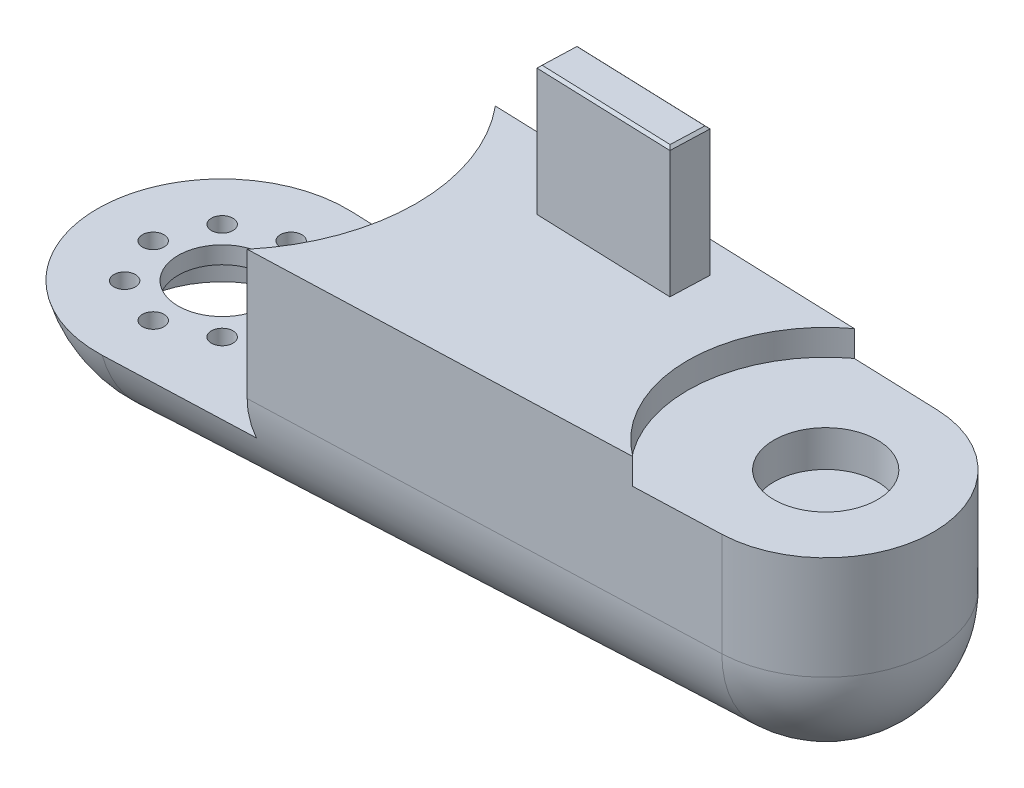
SolidWorks part; units mm, degrees
ref_plane "前视基准面" through (0, 0, 0) normal (0, 0, 1) x (1, 0, 0)
ref_plane "上视基准面" through (0, 0, 0) normal (0, 1, 0) x (1, 0, 0)
ref_plane "右视基准面" through (0, 0, 0) normal (1, 0, 0) x (0, 0, -1)
other "Configuration Table"
sketch "草图1" plane through (0, 0, 0) normal (0, 1, 0) x (1, 0, 0)
  line L2 (0.5357, -14.9904) -> (70.4464, -12.492)
  line L4 (-15, 0) -> (82.5, 0)
  arc A1 (70.4464, -12.492) -> (82.5, 0) centre (70, 0) ccw
  arc A3 (-15, 0) -> (0.5357, -14.9904) centre (0, 0) ccw
  dimension "D1" = 15
  dimension "D2" = 70
  dimension "D3" = 25
ref_axis "基准轴1" through (70, 0, 0) along (-1, 0, 0)
sketch "草图2" plane through (0, 0, 0) normal (0, 1, 0) x (1, 0, 0)
  line L0 (0.5357, 14.9904) -> (70.4464, 12.492)
  line L2 (0.5357, -14.9904) -> (70.4464, -12.492)
  line L3 (82.5, 0) -> (-15, 0)
  line L4 (0.5357, -14.9904) -> (70.4464, -12.492)
  line L5 (82.5, 0) -> (-15, 0)
  arc A2 (70.4464, -12.492) -> (82.5, 0) centre (70, 0) ccw
  arc A3 (-15, 0) -> (0.5357, -14.9904) centre (0, 0) ccw
  arc A4 (70.4464, -12.492) -> (70.4464, 12.492) centre (70, 0) ccw
  arc A5 (0.5357, 14.9904) -> (0.5357, -14.9904) centre (0, 0) ccw
  dimension "D1" = 0
extrude "凸台-拉伸1" add sketch "草图2" along normal blind 15 contours L0 A5 L5 A4 | L5 A5 L4 A4
revolve "旋转1" add sketch "草图1" angle 180 about axis through (70, 0, 0) along (-1, 0, 0)
sketch "草图3" plane through (0, 15, 0) normal (0, 1, 0) x (1, 0, 0)
  line L2 (70.4464, 12.492) -> (0.5357, 14.9904)
  line L3 (0.5357, -14.9904) -> (70.4464, -12.492)
  line L4 (17.2955, 14.3915) -> (0.5357, 14.9904)
  line L5 (0.5357, -14.9904) -> (17.2955, -14.3915)
  arc A0 (17.2955, -14.3915) -> (17.2955, 14.3915) centre (0, 0) ccw
  arc A3 (0.5357, 14.9904) -> (0.5357, -14.9904) centre (0, 0) ccw
  arc A4 (70.4464, -12.492) -> (70.4464, 12.492) centre (70, 0) ccw
  arc A5 (0.5357, 14.9904) -> (0.5357, -14.9904) centre (0, 0) ccw
  dimension "D1" = 45
  dimension "D2" = 0
extrude "切除-拉伸1" cut sketch "草图3" against normal blind 19
sketch "草图4" plane through (0, -4, 0) normal (0, 1, 0) x (1, 0, 0)
  circle A0 centre (0, 0) radius 10
  circle A1 centre (8, 0) radius 1.25
  circle A2 centre (5.6569, -5.6569) radius 1.25
  circle A3 centre (0, -8) radius 1.25
  circle A4 centre (-5.6569, -5.6569) radius 1.25
  circle A5 centre (-8, 0) radius 1.25
  circle A6 centre (-5.6569, 5.6569) radius 1.25
  circle A7 centre (0, 8) radius 1.25
  circle A8 centre (5.6569, 5.6569) radius 1.25
  circle A9 centre (0, 0) radius 5.1
  point P22 (0, 0)
  dimension "D1" = 20
  dimension "D3" = 2.5
  dimension "D5" = 10.2
  dimension "D2" = 8
  dimension "D4" = 8
ref_plane "基准面1" through (0, -6, 0) normal (0, 1, 0) x (1, 0, 0)
sketch "草图5" plane through (0, -6, 0) normal (0, 1, 0) x (1, 0, 0)
  circle A0 centre (0, 0) radius 10 construction
  circle A1 centre (0, 0) radius 10
extrude "切除-拉伸2" cut sketch "草图5" against normal through all
extrude "切除-拉伸3" cut sketch "草图4" against normal through all contours A1 | A2 | A3 | A4 | A5 | A8 | A6 | A7 | A9
sketch "草图11" plane through (0, 15, 0) normal (0, 1, 0) x (1, 0, 0)
  line L0 (70, 0) -> (93.8641, 0) construction
  line L1 (17.2955, 14.3915) -> (70.4464, 12.492) construction
  line L2 (17.2955, -14.3915) -> (70.4464, -12.492) construction
  line L3 (60.4653, 12.8487) -> (70.4464, 12.492)
  line L4 (70.4464, -12.492) -> (60.4653, -12.8487)
  arc A0 (70.4464, -12.492) -> (70.4464, 12.492) centre (70, 0) ccw construction
  arc A1 (70.4464, -12.492) -> (70.4464, 12.492) centre (70, 0) ccw
  arc A2 (60.4653, 12.8487) -> (60.4653, -12.8487) centre (70, 0) ccw
  dimension "D1" = 16
extrude "切除-拉伸5" cut sketch "草图11" against normal blind 3
sketch "草图6" plane through (0, 12, 0) normal (0, 1, 0) x (1, 0, 0)
  arc A0 (70.4464, 12.492) -> (70.4464, -12.492) centre (70, 0) ccw construction
  arc A1 (70.4464, 12.492) -> (70.4464, -12.492) centre (70, 0) ccw
  circle A2 centre (70, 0) radius 3
  circle A3 centre (70, 0) radius 6
  dimension "D1" = 6
  dimension "D2" = 12
extrude "切除-拉伸4" cut sketch "草图6" against normal blind 4.2 contours A3 A2
sketch "草图12" plane through (0, 15, 0) normal (0, 1, 0) x (1, 0, 0)
  line L1 (30.5998, 5.9109) -> (46.5896, 5.3395)
  line L3 (46.5896, 5.3395) -> (46.7503, 9.8366)
  line L8 (46.7503, 9.8366) -> (30.7605, 10.408)
  line L9 (30.7605, 10.408) -> (30.5998, 5.9109)
  line L10 (38.4535, 1.6731) -> (38.9626, 15.9198) construction
  line L11 (17.2955, 14.3915) -> (60.4653, 12.8487) construction
  line L12 (17.2955, 14.3915) -> (60.4653, 12.8487)
  dimension "D5" = 8
  dimension "D1" = 3.5
  dimension "D4" = 8
  dimension "D3" = 4.5
extrude "凸台-拉伸2" add sketch "草图12" along normal blind 15 contours L10 L1 L3 L8 | L1 L10 L8 L9
chamfer "倒角1" distance 0.3 angle 45 4 edges at (30.6802, 30, -8.1595) (38.7554, 30, -10.1223) (46.67, 30, -7.5881) (38.5947, 30, -5.6252)
sketch "草图16" plane through (0.4107, 0, -11.4927) normal (0.0357, 0, -0.9994) x (-0.9994, 0, -0.0357)
  line L0 (-41.3692, 27.5) -> (-35.3692, 27.5)
hole_wizard "孔1" positions "草图17" profile "草图18" legacy
sketch "草图17" plane through (0.4107, 0, -11.4927) normal (0.0357, 0, -0.9994) x (-0.9994, 0, -0.0357)
  point P0 (-41.3692, 27.5)
  point P3 (-35.3692, 27.5)
sketch "草图18" plane through (41.7535, 27.5, -10.0152) normal (0, 1, 0) x (-0.9994, 0, -0.0357)
  line L0 (0, 0) -> (0, 3.5)
  line L1 (0, 3.5) -> (0.85, 3.5)
  line L2 (0.85, 3.5) -> (0.85, 0)
  line L3 (0.85, 0) -> (0, 0)
  line L4 (0, 110) -> (0, -10) construction
  dimension "直径" = 1.7
  dimension "深度" = 3.5
